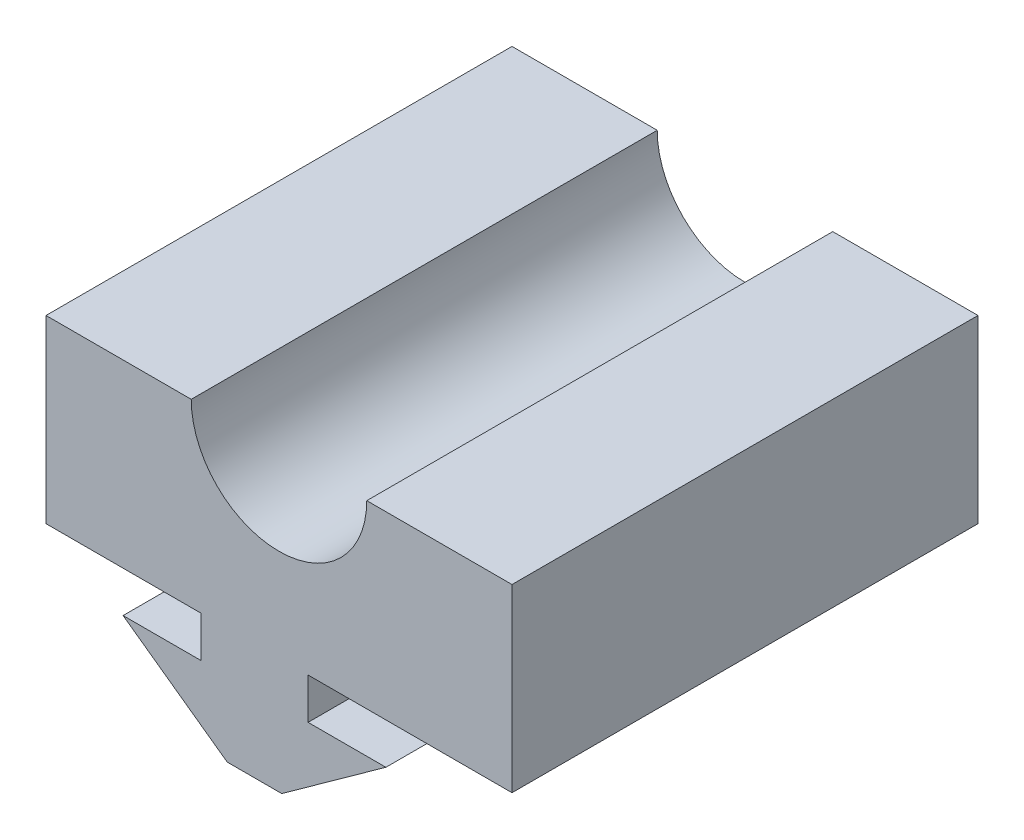
SolidWorks part; units mm, degrees
ref_plane "Front Plane" through (0, 0, 0) normal (0, 0, 1) x (1, 0, 0)
ref_plane "Top Plane" through (0, 0, 0) normal (0, 1, 0) x (1, 0, 0)
ref_plane "Right Plane" through (0, 0, 0) normal (1, 0, 0) x (0, 0, -1)
sketch "Sketch1" plane through (0, 0, 0) normal (0, 0, 1) x (1, 0, 0)
  line L0 (0, 0) -> (8.443, 0)
  line L5 (25.4, 0) -> (25.4, 9.8295)
  line L6 (0, 0) -> (0, 9.8295)
  line L7 (0, 9.8295) -> (7.9158, 9.8295)
  line L8 (17.4842, 9.8295) -> (25.4, 9.8295)
  line L9 (25.4, 0) -> (14.285, 0)
  line L10 (14.285, 0) -> (14.285, -2.2352)
  line L11 (14.285, -2.2352) -> (18.5268, -2.2352)
  line L12 (18.5268, -2.2352) -> (12.8499, -6.3153)
  line L13 (12.8499, -6.3153) -> (9.8781, -6.3153)
  line L14 (9.8781, -6.3153) -> (4.2012, -2.2352)
  line L15 (4.2012, -2.2352) -> (8.443, -2.2352)
  line L16 (8.443, -2.2352) -> (8.443, 0)
  arc A0 (7.9158, 9.8295) -> (17.4842, 9.8295) centre (12.7, 9.8295) ccw
  point P15 (14.9964, -1.3297)
  point P17 (6.4467, -1.5986)
  point P18 (14.7544, -4.4216)
  point P19 (14.5393, -2.5127)
  point P20 (8.3643, -2.5889)
  dimension "D1" = 25.4
  dimension "D2" = 5.842
  dimension "D3" = 2.9718
  dimension "D4" = 14.3256
  dimension "D5" = 2.2352
extrude "Boss-Extrude1" add sketch "Sketch1" along normal blind 25.4
